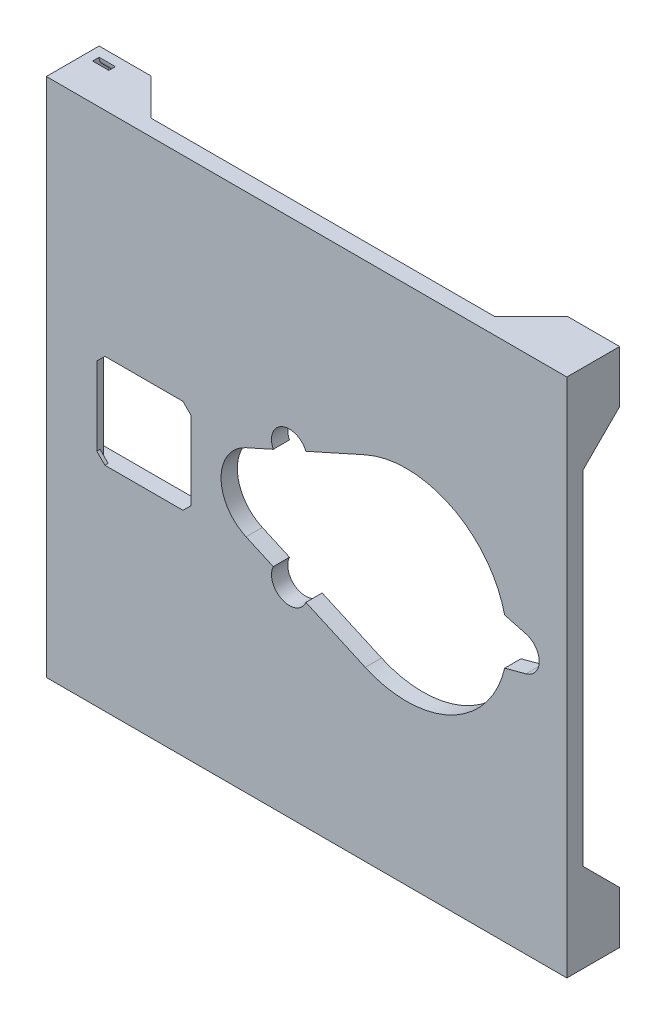
SolidWorks part; units mm, degrees
ref_plane "Front Plane" through (0, 0, 0) normal (1, 0, 0) x (0, 1, 0)
ref_plane "Top Plane" through (0, 0, 0) normal (0, 0, 1) x (0, 1, 0)
ref_plane "Right Plane" through (0, 0, 0) normal (0, 1, 0) x (-1, 0, 0)
sketch "Sketch1" plane through (0, 0, 0) normal (0, 0, 1) x (0, 1, 0)
  line L0 (80, 0) -> (80, 49.3) construction
  line L1 (0, 0) -> (160, 0)
  line L2 (0, 0) -> (0, 160)
  line L3 (0, 160) -> (160, 160)
  line L4 (160, 0) -> (160, 160)
  line L5 (80, 49.3) -> (80, 93.3) construction
  line L6 (68.1376, 98.6182) -> (64.388, 90.2545)
  line L7 (91.8624, 98.6182) -> (95.612, 90.2545)
  line L8 (80, 49.3) -> (80, 85.3) construction
  line L9 (62, 85.3) -> (98, 85.3) construction
  line L10 (80, 49.3) -> (80, 14) construction
  line L11 (59.8897, 80.221) -> (51.7127, 61.9818)
  line L12 (100.1103, 80.221) -> (108.2873, 61.9818)
  line L13 (85.3126, 12.5765) -> (87.0648, 19.1158)
  line L14 (74.6874, 12.5765) -> (72.9352, 19.1158)
  line L15 (80, 160) -> (80, 130) construction
  line L17 (65.5, 144.5) -> (94.5, 144.5)
  line L18 (65.5, 144.5) -> (65.5, 115.5)
  line L19 (65.5, 115.5) -> (94.5, 115.5)
  line L20 (94.5, 144.5) -> (94.5, 115.5)
  line L21 (65.5, 144.5) -> (94.5, 115.5) construction
  line L22 (65.5, 115.5) -> (94.5, 144.5) construction
  arc A0 (51.7127, 61.9818) -> (72.9352, 19.1158) centre (80, 49.3) ccw
  arc A1 (91.8624, 98.6182) -> (68.1376, 98.6182) centre (80, 93.3) ccw
  arc A2 (64.388, 90.2545) -> (59.8897, 80.221) centre (62, 85.3) ccw
  arc A3 (100.1103, 80.221) -> (95.612, 90.2545) centre (98, 85.3) ccw
  circle A4 centre (80, 93.3) radius 12.25 construction
  circle A5 centre (80, 49.3) radius 30 construction
  circle A6 centre (62, 85.3) radius 4.5 construction
  circle A7 centre (98, 85.3) radius 4.5 construction
  circle A8 centre (80, 14) radius 4.5 construction
  arc A9 (74.6874, 12.5765) -> (85.3126, 12.5765) centre (80, 14) ccw
  arc A10 (87.0648, 19.1158) -> (108.2873, 61.9818) centre (80, 49.3) ccw
  point P18 (80, 85.3)
  dimension "D4" = 44
  dimension "D5" = 62
  dimension "D6" = 26
  dimension "D7" = 36
  dimension "D9" = 11
  dimension "D10" = 11
  dimension "D11" = 24.5
  dimension "D12" = 60
  dimension "D13" = 9
  dimension "D14" = 9
  dimension "D15" = 35.3
  dimension "D16" = 9
  dimension "D17" = 11
  dimension "D19" = 30
  dimension "D1" = 160
  dimension "D2" = 160
  dimension "D3" = 49.3
  dimension "D8" = 36
  dimension "D18" = 6.7699
  dimension "D20" = 29
  dimension "D21" = 29
extrude "Boss-Extrude1" add sketch "Sketch1" along normal blind 5
sketch "Sketch2" plane through (0, 0, 5) normal (0, 0, 1) x (1, 0, 0)
  line L0 (-152, 8) -> (-8, 8)
  line L1 (-8, 8) -> (-8, 152)
  line L2 (-8, 152) -> (-152, 152)
  line L3 (-152, 152) -> (-152, 8)
  line L4 (-160, 0) -> (0, 0)
  line L5 (0, 0) -> (0, 160)
  line L6 (0, 160) -> (-160, 160)
  line L7 (-160, 160) -> (-160, 0)
  line L8 (-160, 0) -> (0, 0)
  line L9 (0, 0) -> (0, 160)
  line L10 (0, 160) -> (-160, 160)
  line L11 (-160, 160) -> (-160, 0)
  dimension "D1" = 0
  dimension "D2" = 8
sketch "Sketch3" plane through (0, 0, 5) normal (0, 0, 1) x (1, 0, 0)
  line L0 (-144.5, 92) -> (-142, 94.5)
  line L1 (-144.5, 94.5) -> (-142, 94.5)
  line L2 (-144.5, 94.5) -> (-144.5, 92)
  line L5 (-144.5, 65.5) -> (-142, 65.5)
  line L6 (-144.5, 65.5) -> (-115.5, 65.5) construction
  line L7 (-115.5, 65.5) -> (-118, 65.5)
  line L8 (-115.5, 65.5) -> (-115.5, 68)
  line L9 (-115.5, 65.5) -> (-115.5, 94.5) construction
  line L10 (-144.5, 65.5) -> (-144.5, 68)
  line L11 (-144.5, 94.5) -> (-144.5, 65.5) construction
  line L12 (-115.5, 94.5) -> (-115.5, 92)
  line L13 (-115.5, 94.5) -> (-118, 94.5)
  line L14 (-115.5, 94.5) -> (-144.5, 94.5) construction
  line L15 (-144.5, 68) -> (-142, 65.5)
  line L16 (-115.5, 68) -> (-118, 65.5)
  line L17 (-118, 94.5) -> (-115.5, 92)
  dimension "D1" = 2.5
  dimension "D2" = 2.5
  dimension "D3" = 2.5
  dimension "D4" = 2.5
  dimension "D5" = 2.5
  dimension "D6" = 2.5
  dimension "D7" = 2.5
  dimension "D8" = 2.5
extrude "Boss-Extrude2" add sketch "Sketch3" against normal blind 1
sketch "Sketch4" plane through (0, 0, 5) normal (0, 0, 1) x (1, 0, 0)
  line L1 (-160, 160) -> (-156, 160) construction
  line L2 (-160, 160) -> (-160, 156) construction
  line L3 (-160, 156) -> (-156, 156) construction
  line L4 (-156, 160) -> (-156, 156) construction
  line L5 (0, 160) -> (-4, 160) construction
  line L6 (0, 160) -> (0, 156) construction
  line L7 (0, 156) -> (-4, 156) construction
  line L8 (-4, 160) -> (-4, 156) construction
  line L9 (0, 0) -> (-4, 0) construction
  line L10 (0, 0) -> (0, 4) construction
  line L11 (0, 4) -> (-4, 4) construction
  line L12 (-4, 0) -> (-4, 4) construction
  line L13 (-160, 0) -> (-156, 0) construction
  line L14 (-160, 0) -> (-160, 4) construction
  line L15 (-160, 4) -> (-156, 4) construction
  line L16 (-156, 0) -> (-156, 4) construction
  circle A0 centre (-156, 156) radius 1
  circle A1 centre (-4, 156) radius 1
  circle A2 centre (-4, 4) radius 1
  circle A3 centre (-156, 4) radius 1
  dimension "D9" = 2
  dimension "D1" = 4
  dimension "D2" = 4
  dimension "D3" = 4
  dimension "D4" = 4
  dimension "D5" = 4
  dimension "D6" = 4
  dimension "D7" = 4
  dimension "D8" = 4
sketch "Sketch5" plane through (0, 0, 0) normal (0, 0, -1) x (1, 0, 0)
  line L0 (-144.5, -94.5) -> (-149.5, -94.5) construction
  line L6 (-144.5, -65.5) -> (-149.5, -65.5)
  line L7 (-144.5, -65.5) -> (-144.5, -94.5)
  line L8 (-144.5, -94.5) -> (-149.5, -94.5)
  line L9 (-149.5, -65.5) -> (-149.5, -94.5)
  dimension "D1" = 5
extrude "Cut-Extrude2" cut sketch "Sketch5" against normal blind 3
sketch "Sketch6" plane through (0, 0, 0) normal (0, 0, -1) x (1, 0, 0)
  line L0 (-160, -16) -> (-160, 0)
  line L1 (-160, 0) -> (-144, 0) construction
  line L2 (-160, 0) -> (-160, -16) construction
  line L3 (-160, -16) -> (-144, -16) construction
  line L4 (-144, 0) -> (-144, -16) construction
  line L5 (0, 0) -> (-16, 0) construction
  line L6 (0, 0) -> (0, -16) construction
  line L7 (0, -16) -> (-16, -16) construction
  line L8 (-16, 0) -> (-16, -16) construction
  line L9 (-160, -160) -> (-144, -160) construction
  line L10 (-160, -160) -> (-160, -144) construction
  line L11 (-160, -144) -> (-144, -144) construction
  line L12 (-144, -160) -> (-144, -144) construction
  line L13 (0, -160) -> (-16, -160) construction
  line L14 (0, -160) -> (0, -144) construction
  line L15 (0, -144) -> (-16, -144) construction
  line L16 (-16, -160) -> (-16, -144) construction
  line L17 (-160, 0) -> (-144, 0)
  line L18 (-144, 0) -> (-160, -16)
  line L19 (-144, -160) -> (-160, -160)
  line L20 (-160, -160) -> (-160, -144)
  line L21 (-160, -144) -> (-144, -160)
  line L22 (0, -160) -> (-16, -160)
  line L23 (-16, -160) -> (0, -144)
  line L24 (0, -144) -> (0, -160)
  line L25 (0, 0) -> (-16, 0)
  line L26 (-16, 0) -> (0, -16)
  line L27 (0, -16) -> (0, 0)
  dimension "D1" = 16
  dimension "D2" = 16
  dimension "D3" = 16
  dimension "D4" = 16
  dimension "D5" = 16
  dimension "D6" = 16
  dimension "D7" = 16
  dimension "D8" = 16
extrude "Boss-Extrude3" add sketch "Sketch6" along normal blind 11.22
sketch "Sketch11" plane through (0, 0, 0) normal (0, 0, -1) x (1, 0, 0)
  line L0 (0, -144) -> (0, -132.78) construction
  line L1 (0, -16) -> (0, -144) construction
  line L2 (-16, -160) -> (-27.22, -160) construction
  line L3 (-16, -160) -> (-144, -160) construction
  line L4 (0, -132.78) -> (-27.22, -160) construction
  line L5 (0, -144) -> (-16, -160) construction
  line L6 (-16, 0) -> (-27.22, 0) construction
  line L7 (-144, 0) -> (-16, 0) construction
  line L8 (0, -16) -> (0, -27.22) construction
  line L9 (-144, 0) -> (-132.78, 0) construction
  line L10 (-160, -16) -> (-160, -27.22) construction
  line L11 (-160, -144) -> (-160, -16) construction
  line L12 (-160, -144) -> (-160, -132.78) construction
  line L13 (-144, -160) -> (-132.78, -160) construction
  dimension "D1" = 11.22
ref_plane "Plane6" through (44.26, 44.26, 44.26) normal (0.5774, 0.5774, 0.5774) x (0.8165, -0.4082, -0.4082)
sketch "Sketch12" plane through (44.26, 44.26, 44.26) normal (0.5774, 0.5774, 0.5774) x (0.8165, -0.4082, -0.4082)
  line L3 (-54.2072, 93.8896) -> (-87.5448, 113.1371)
  line L4 (-54.2072, 93.8896) -> (-54.2072, 109.7571)
  line L5 (-54.2072, 109.7571) -> (-73.8031, 121.0708)
  line L6 (-73.8031, 121.0708) -> (-87.5448, 113.1371)
extrude "Boss-Extrude5" add sketch "Sketch12" along normal up to vertex (6.4779 mm away) up to point (0, 144, 0)
ref_plane "Plane7" through (-97.5933, 97.5933, 97.5933) normal (-0.5774, 0.5774, 0.5774) x (0.4082, -0.4082, 0.8165)
ref_plane "Plane8" through (-44.26, -44.26, 44.26) normal (-0.5774, -0.5774, 0.5774) x (0.4082, 0.4082, 0.8165)
ref_plane "Plane9" through (-9.0733, 9.0733, -9.0733) normal (0.5774, -0.5774, 0.5774) x (-0.8165, -0.4082, 0.4082)
sketch "Sketch13" plane through (-97.5933, 97.5933, 97.5933) normal (-0.5774, 0.5774, 0.5774) x (0.4082, -0.4082, 0.8165)
  line L0 (-133.2686, 11.3137) -> (-119.5269, 19.2474)
  line L1 (-119.5269, 19.2474) -> (-119.5269, -19.2474)
  line L2 (-119.5269, -19.2474) -> (-133.2686, -11.3137)
  line L3 (-133.2686, -11.3137) -> (-133.2686, 11.3137)
extrude "Boss-Extrude6" add sketch "Sketch13" along normal up to vertex (6.4779 mm away) up to point (-160, 144, 0)
sketch "Sketch14" plane through (-44.26, -44.26, 44.26) normal (-0.5774, -0.5774, 0.5774) x (0.4082, 0.4082, 0.8165)
  line L0 (-54.2072, 132.3845) -> (-67.9488, 124.4508)
  line L1 (-67.9488, 124.4508) -> (-67.9488, 101.8234)
  line L2 (-67.9488, 101.8234) -> (-54.2072, 93.8896)
  line L3 (-54.2072, 93.8896) -> (-54.2072, 132.3845)
extrude "Boss-Extrude7" add sketch "Sketch14" along normal up to vertex (6.4779 mm away) up to point (-144, 0, 0)
sketch "Sketch15" plane through (-9.0733, 9.0733, -9.0733) normal (0.5774, -0.5774, 0.5774) x (-0.8165, -0.4082, 0.4082)
  line L0 (-11.1125, -19.2474) -> (22.225, 0)
  line L4 (22.225, 0) -> (8.4834, 7.9337)
  line L5 (8.4834, 7.9337) -> (-11.1125, -3.38)
  line L6 (-11.1125, -3.38) -> (-11.1125, -19.2474)
extrude "Boss-Extrude8" add sketch "Sketch15" along normal up to vertex (6.4779 mm away) up to point (0, 16, 0)
sketch "Sketch16" plane through (0, 0, 5) normal (0, 0, 1) x (1, 0, 0)
  line L0 (-170, -10) -> (10, -10)
  line L1 (10, -10) -> (10, 170)
  line L2 (10, 170) -> (-170, 170)
  line L3 (-170, 170) -> (-170, -10)
  line L4 (-160, 0) -> (0, 0)
  line L5 (0, 0) -> (0, 160)
  line L6 (0, 160) -> (-160, 160)
  line L7 (-160, 160) -> (-160, 0)
  line L8 (-160, 0) -> (0, 0)
  line L9 (0, 0) -> (0, 160)
  line L10 (0, 160) -> (-160, 160)
  line L11 (-160, 160) -> (-160, 0)
  dimension "D1" = 0
  dimension "D2" = 10
extrude "Cut-Extrude3" cut sketch "Sketch16" against normal blind 47
sketch "Sketch18" plane through (0, 0, -11.22) normal (0, 0, -1) x (1, 0, 0)
  line L9 (0, 0) -> (-3, 0) construction
  line L10 (0, 0) -> (0, -3) construction
  line L11 (0, -3) -> (-3, -3) construction
  line L12 (-3, 0) -> (-3, -3) construction
  line L13 (-3, -3) -> (-8, -3)
  line L14 (-3, -3) -> (-3, -5)
  line L15 (-3, -5) -> (-8, -5)
  line L16 (-8, -3) -> (-8, -5)
  dimension "D1" = 3
  dimension "D2" = 3
  dimension "D3" = 2
  dimension "D4" = 5
revolve "Cut-Revolve1" cut sketch "Sketch18" angle 360
sketch "Sketch19" plane through (0, 0, -11.22) normal (0, 0, -1) x (1, 0, 0)
  line L9 (-160, -160) -> (-157, -160) construction
  line L10 (-160, -160) -> (-160, -157) construction
  line L11 (-160, -157) -> (-157, -157) construction
  line L12 (-157, -160) -> (-157, -157) construction
  line L13 (-157, -157) -> (-152, -157)
  line L14 (-157, -157) -> (-157, -155)
  line L15 (-157, -155) -> (-152, -155)
  line L16 (-152, -157) -> (-152, -155)
  dimension "D1" = 3
  dimension "D2" = 3
  dimension "D3" = 2
  dimension "D4" = 5
revolve "Cut-Revolve2" cut sketch "Sketch19" angle 360
